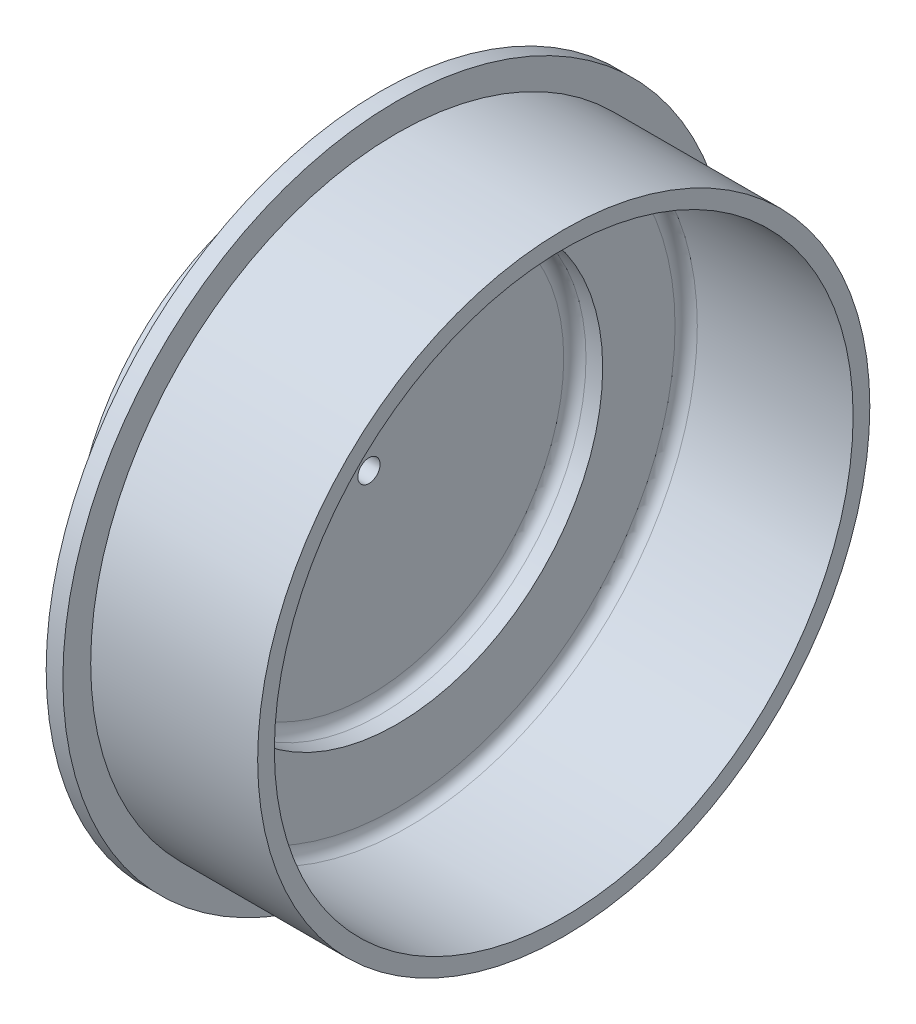
SolidWorks part; units mm, degrees
ref_plane "Front Plane" through (0, 0, 0) normal (0, 0, 1) x (1, 0, 0)
ref_plane "Top Plane" through (0, 0, 0) normal (0, 1, 0) x (1, 0, 0)
ref_plane "Right Plane" through (0, 0, 0) normal (1, 0, 0) x (0, 0, -1)
sketch "Sketch1" plane through (0, 0, 0) normal (0, 0, 1) x (1, 0, 0)
  line L0 (0, 40) -> (0, 37)
  line L1 (0, 37) -> (8, 37)
  line L2 (10, 35) -> (10, 2)
  line L3 (10, 2) -> (13, 2)
  line L4 (13, 2) -> (13, 35)
  line L5 (15, 37) -> (18, 37)
  line L6 (18, 37) -> (18, 50)
  line L7 (20, 52) -> (48, 52)
  line L8 (48, 52) -> (48, 55)
  line L9 (48, 55) -> (18, 55)
  line L10 (15, 52) -> (15, 40)
  line L11 (15, 40) -> (0, 40)
  line L12 (0, 0) -> (13, 0) construction
  line L15 (15, 52) -> (15, 60)
  line L16 (15, 60) -> (18, 60)
  line L17 (18, 55) -> (18, 60)
  arc A0 (18, 50) -> (20, 52) centre (20, 50) cw
  arc A1 (13, 35) -> (15, 37) centre (15, 35) cw
  arc A2 (10, 35) -> (8, 37) centre (8, 35) ccw
  point P3 (16.5, 37)
  point P14 (0, 38.5)
  dimension "D12" = 2
  dimension "D1" = 2
  dimension "D2" = 3
  dimension "D3" = 3
  dimension "D4" = 3
  dimension "D5" = 3
  dimension "D6" = 40
  dimension "D7" = 3
  dimension "D8" = 10
  dimension "D9" = 5
  dimension "D10" = 55
  dimension "D11" = 15
  dimension "D13" = 30
  dimension "D14" = 3
revolve "Revolve1" add sketch "Sketch1" angle 360 about L12
